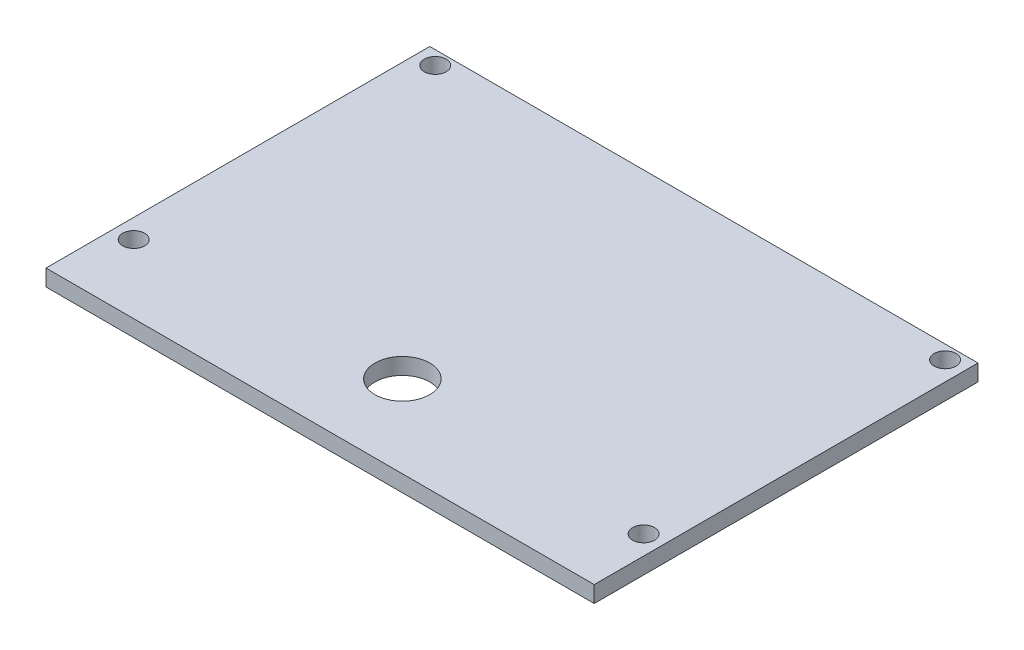
SolidWorks part; units mm, degrees
material "ABS PC"
ref_plane "Front Plane" through (0, 0, 0) normal (0, 0, 1) x (1, 0, 0)
ref_plane "Top Plane" through (0, 0, 0) normal (0, 1, 0) x (1, 0, 0)
ref_plane "Right Plane" through (0, 0, 0) normal (1, 0, 0) x (0, 0, -1)
sketch "Sketch1" plane through (0, 0, 0) normal (0, 1, 0) x (1, 0, 0)
  line L1 (-14.4451, 7.0497) -> (85.5549, 7.0497)
  line L2 (-14.4451, 7.0497) -> (-14.4451, -62.9503)
  line L3 (-14.4451, -62.9503) -> (85.5549, -62.9503)
  line L4 (85.5549, 7.0497) -> (85.5549, -62.9503)
  circle A0 centre (-10.9451, 4.5497) radius 2
  circle A1 centre (82.0549, 4.5497) radius 2
  circle A2 centre (-10.9451, -50.4503) radius 2
  circle A3 centre (82.0549, -50.4503) radius 2
  circle A4 centre (35.5549, -47.9503) radius 5
  dimension "D3" = 93
  dimension "D7" = 50
  dimension "D1" = 100
  dimension "D2" = 70
  dimension "D4" = 3.5
  dimension "D5" = 55
  dimension "D6" = 2.5
  dimension "D8" = 15
extrude "Boss-Extrude1" add sketch "Sketch1" along normal blind 3
